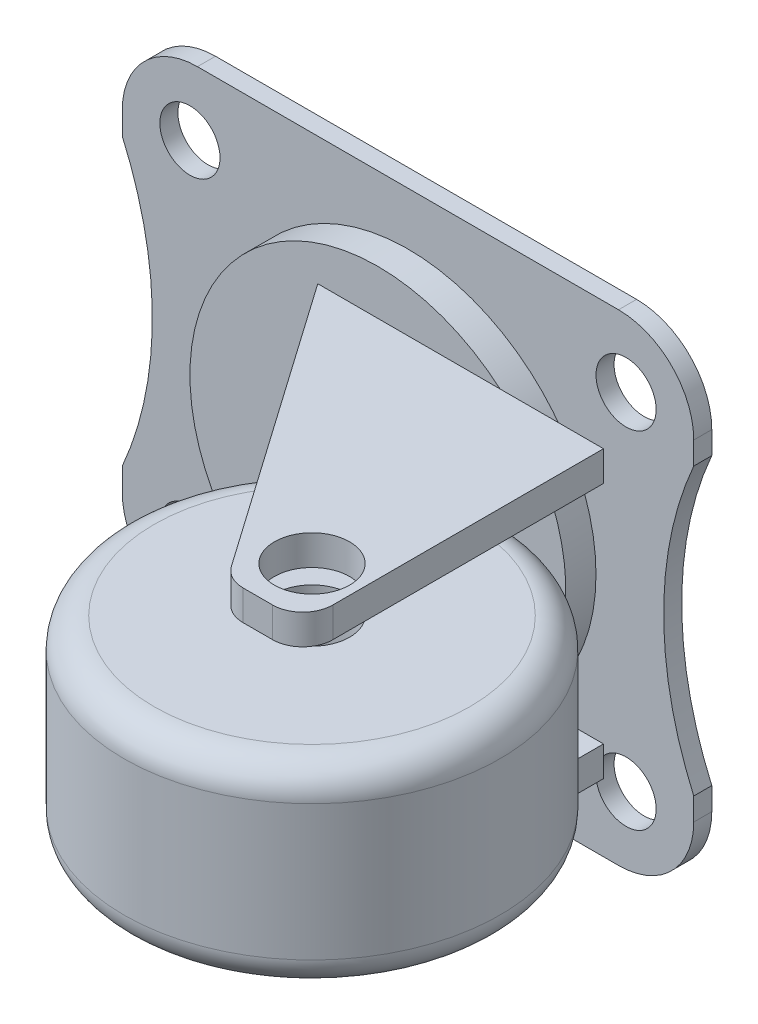
SolidWorks part; units mm, degrees
ref_plane "前视基准面" through (0, 0, 0) normal (0, 0, 1) x (1, 0, 0)
ref_plane "上视基准面" through (0, 0, 0) normal (0, 1, 0) x (1, 0, 0)
ref_plane "右视基准面" through (0, 0, 0) normal (1, 0, 0) x (0, 0, -1)
sketch "草图1" plane through (0, 0, 0) normal (0, 0, 1) x (1, 0, 0)
  line L1 (0, 0) -> (50, 0)
  line L2 (0, 0) -> (0, -50)
  line L3 (0, -50) -> (50, -50)
  line L4 (50, 0) -> (50, -50)
  dimension "D1" = 50
  dimension "D2" = 50
extrude "凸台-拉伸1" add sketch "草图1" along normal blind 1.2
sketch "草图2" plane through (0, 0, 1.2) normal (0, 0, 1) x (1, 0, 0)
  line L0 (0, -25) -> (50, -25) construction
  line L1 (0, 0) -> (0, -50) construction
  line L2 (50, -50) -> (50, 0) construction
  line L3 (25, 0) -> (25, -50) construction
  line L4 (50, 0) -> (0, 0) construction
  line L5 (0, -50) -> (50, -50) construction
  line L6 (6, -9) -> (44, -9)
  line L7 (44, -9) -> (44, -15.5)
  line L8 (6, -41) -> (44, -41)
  line L9 (44, -41) -> (44, -34.5)
  line L10 (6, -41) -> (6, -34.5)
  line L11 (6, -9) -> (6, -15.5)
  line L12 (50, -50) -> (50, 0)
  line L13 (0, -50) -> (50, -50)
  line L14 (0, 0) -> (0, -50)
  line L15 (50, 0) -> (0, 0)
  arc A0 (44, -15.5) -> (44, -34.5) centre (65.5625, -25) ccw
  arc A1 (6, -15.5) -> (6, -34.5) centre (-15.5625, -25) cw
  circle A2 centre (10.5, -13.5) radius 2
  circle A3 centre (39.5, -13.5) radius 2
  circle A4 centre (39.5, -36.5) radius 2
  circle A5 centre (10.5, -36.5) radius 2
  line M7 (0, 0) -> (0, -50)
  line M8 (0, -50) -> (50, -50)
  line M9 (50, -50) -> (50, 0)
  line M10 (50, 0) -> (0, 0)
  dimension "D3" = 34
  dimension "D5" = 29
  dimension "D6" = 23
  dimension "D7" = 4
  dimension "D1" = 38
  dimension "D2" = 32
  dimension "D4" = 19
extrude "切除-拉伸1" cut sketch "草图2" against normal blind 1.2 contours A1 L11 L6 L7 A0 L9 L8 L10 M10 M7 M8 M9 | A3 | A5 | A2 | A4
fillet "圆角3" radius 5 4 edges at (6, -41, 0.6) (44, -41, 0.6) (6, -9, 0.6) (44, -9, 0.6)
sketch "草图3" plane through (0, 0, 1.2) normal (0, 0, 1) x (1, 0, 0)
  line L0 (8, -25) -> (42, -25) construction
  line L1 (25, -9) -> (25, -41) construction
  line L2 (11, -9) -> (39, -9) construction
  line L3 (11, -41) -> (39, -41) construction
  arc A0 (6, -34.5) -> (6, -15.5) centre (-15.5625, -25) ccw construction
  arc A1 (44, -15.5) -> (44, -34.5) centre (65.5625, -25) ccw construction
  circle A2 centre (25, -25) radius 12.5
  dimension "D1" = 25
extrude "凸台-拉伸2" add sketch "草图3" along normal blind 2
sketch "草图4" plane through (0, 0, 3.2) normal (0, 0, 1) x (1, 0, 0)
  line L0 (37.5, -25) -> (12.5, -25) construction
  line L1 (40, -34.5) -> (15, -34.5)
  line L2 (40, -34.5) -> (40, -32.5)
  line L3 (40, -32.5) -> (15, -32.5)
  line L4 (15, -34.5) -> (15, -32.5)
  line L5 (25, -37.5) -> (25, -12.5) construction
  line L6 (15, -15.5) -> (15, -17.5)
  line L7 (40, -15.5) -> (40, -17.5)
  line L8 (40, -17.5) -> (15, -17.5)
  line L9 (40, -15.5) -> (15, -15.5)
  circle A0 centre (25, -25) radius 12.5 construction
  circle A1 centre (25, -25) radius 12.5 construction
  dimension "D1" = 15
  dimension "D2" = 2
  dimension "D3" = 25
  dimension "D4" = 10
extrude "凸台-拉伸3" add sketch "草图4" along normal blind 20
sketch "草图5" plane through (0, -34.5, 0) normal (0, -1, 0) x (1, 0, 0)
  line L0 (35, 23.2) -> (21, 3.2)
  line L1 (15, 23.2) -> (40, 23.2) construction
  line L2 (33.124, 3.2) -> (16.876, 3.2) construction
  line L3 (21, 3.2) -> (15, 3.2)
  line L4 (15, 23.2) -> (15, 3.2) construction
  line L5 (15, 3.2) -> (16.876, 3.2) construction
  line L6 (15, 3.2) -> (15, 23.2)
  line L7 (15, 23.2) -> (35, 23.2)
  dimension "D1" = 20
  dimension "D2" = 6
extrude "切除-拉伸2" cut sketch "草图5" against normal blind 23
ref_plane "基准面1" through (0, -25, 0) normal (0, 1, 0) x (1, 0, 0)
sketch "草图6" plane through (0, -25, 0) normal (0, 1, 0) x (1, 0, 0)
  line L0 (11, 0) -> (39, 0) construction
  circle A0 centre (36.9169, -19.5) radius 12.5
  circle A1 centre (36.9169, -19.5) radius 2.5
  dimension "D1" = 25
  dimension "D2" = 5
  dimension "D3" = 19.5
extrude "凸台-拉伸4" add sketch "草图6" along normal mid plane 13 separate body
fillet "圆角4" radius 2 2 edges at (36.9169, -18.5, 32) (36.9169, -31.5, 32)
fillet "圆角5" radius 2 4 edges at (35, -16.5, 23.2) (40, -16.5, 23.2) (35, -33.5, 23.2) (40, -33.5, 23.2)
sketch "草图7" plane through (0, -34.5, 0) normal (0, -1, 0) x (1, 0, 0)
  circle A0 centre (36.9169, 19.5) radius 2.5 construction
  circle A1 centre (36.9169, 19.5) radius 2.5
extrude "切除-拉伸3" cut sketch "草图7" against normal blind 21
